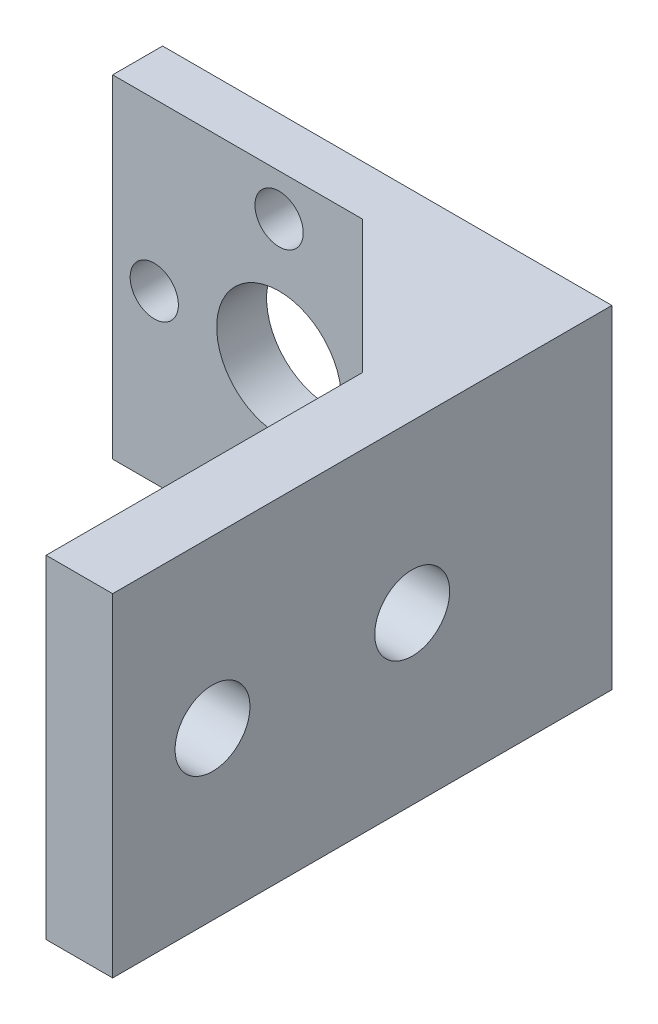
SolidWorks part; units mm, degrees
material "ABS"
ref_plane "前基準面" through (0, 0, 0) normal (0, 0, 1) x (1, 0, 0)
ref_plane "上基準面" through (0, 0, 0) normal (0, 1, 0) x (1, 0, 0)
ref_plane "右基準面" through (0, 0, 0) normal (1, 0, 0) x (0, 0, -1)
sketch "草圖1" plane through (0, 0, 0) normal (0, 0, 1) x (1, 0, 0)
  line L1 (-10, -10) -> (10, -10)
  line L2 (-10, -10) -> (-10, 10)
  line L3 (-10, 10) -> (10, 10)
  line L4 (10, -10) -> (10, 10)
  line L5 (-10, -10) -> (10, 10) construction
  line L6 (-10, 10) -> (10, -10) construction
  point P0 (0, 0)
  dimension "D1" = 20
  dimension "D2" = 20
extrude "填料-伸長1" add sketch "草圖1" along normal blind 3
sketch "草圖8" plane through (10, 0, 0) normal (1, 0, 0) x (0, 0, -1)
  line L0 (0, -10) -> (0, 10) construction
  line L1 (-3, 10) -> (0, 10)
  line L2 (-3, 10) -> (-3, -10)
  line L3 (-3, -10) -> (0, -10)
  line L4 (0, 10) -> (0, -10)
extrude "填料-伸長3" add sketch "草圖8" along normal blind 3
sketch "草圖2" plane through (0, 0, 3) normal (0, 0, 1) x (1, 0, 0)
  circle A0 centre (0, 0) radius 3.75
  dimension "D1" = 7.5
extrude "除料-伸長1" cut sketch "草圖2" against normal through all
sketch "草圖3" plane through (0, 0, 0) normal (0, 0, -1) x (-1, 0, 0)
  line L1 (-13, 10) -> (-17, 10)
  line L2 (-13, 10) -> (-13, -10)
  line L3 (-13, -10) -> (-17, -10)
  line L4 (-17, 10) -> (-17, -10)
  dimension "D1" = 4
extrude "填料-伸長2" add sketch "草圖3" against normal blind 30
chamfer "導角1" distance 8 angle 45 1 edges at (13, 0, 3)
sketch "草圖9" plane through (0, 0, 30) normal (0, 0, 1) x (1, 0, 0)
  circle A0 centre (0, 0) radius 10.5
  dimension "D1" = 21
extrude "除料-伸長2" cut sketch "草圖9" against normal up to surface (27 mm away) up to face at (3.75, 0, 3)
hole_wizard "M4 凹頭蓋螺釘的柱孔1" positions "草圖4" profile "草圖5" counterbore size "M4" standard "Ansi Metric" end condition through all
sketch "草圖4" plane through (-10, 0, 0) normal (-1, 0, 0) x (0, 0, 1)
  line L0 (0, 0) -> (30, 0) construction
  line L1 (30, -10) -> (30, 10) construction
  point P9 (12, 0)
  point P11 (24, 0)
  dimension "D1" = 12
  dimension "D2" = 6
sketch "草圖5" plane through (-10, 0, 24) normal (0, 1, 0) x (0, 0, 1)
  line L0 (0, 0) -> (0, 27)
  line L1 (0, 27) -> (2.25, 27)
  line L3 (2.25, 27) -> (2.25, 23)
  line L4 (2.25, 23) -> (4, 23)
  line L5 (4, 23) -> (4, 0)
  line L7 (4, 0) -> (0, 0)
  line L11 (0, -6.35) -> (0, 107.95) construction
  dimension "貫穿孔直徑" = 4.5
  dimension "貫穿孔深度" = 27
  dimension "柱孔直徑" = 8
  dimension "柱孔深度" = 23
hole_wizard "M2.5 餘隙孔1" positions "草圖6" profile "草圖7" hole size "M2.5" standard "Ansi Metric" end condition through all
sketch "草圖6" plane through (0, 0, 0) normal (0, 0, -1) x (-1, 0, 0)
  circle A0 centre (0, 0) radius 7.5 construction
  point P4 (0, 7.5)
  point P6 (-7.5, 0)
  point P8 (7.5, 0)
  point P10 (0, -7.5)
  dimension "D1" = 15
sketch "草圖7" plane through (0, -7.5, 0) normal (1, 0, 0) x (0, 1, 0)
  line L0 (0, 0) -> (0, 30)
  line L1 (0, 30) -> (1.45, 30)
  line L2 (1.45, 30) -> (1.45, 0)
  line L5 (1.45, 0) -> (0, 0)
  line L11 (0, -6.35) -> (0, 107.95) construction
  dimension "貫穿孔直徑" = 2.9
  dimension "貫穿孔深度" = 30
